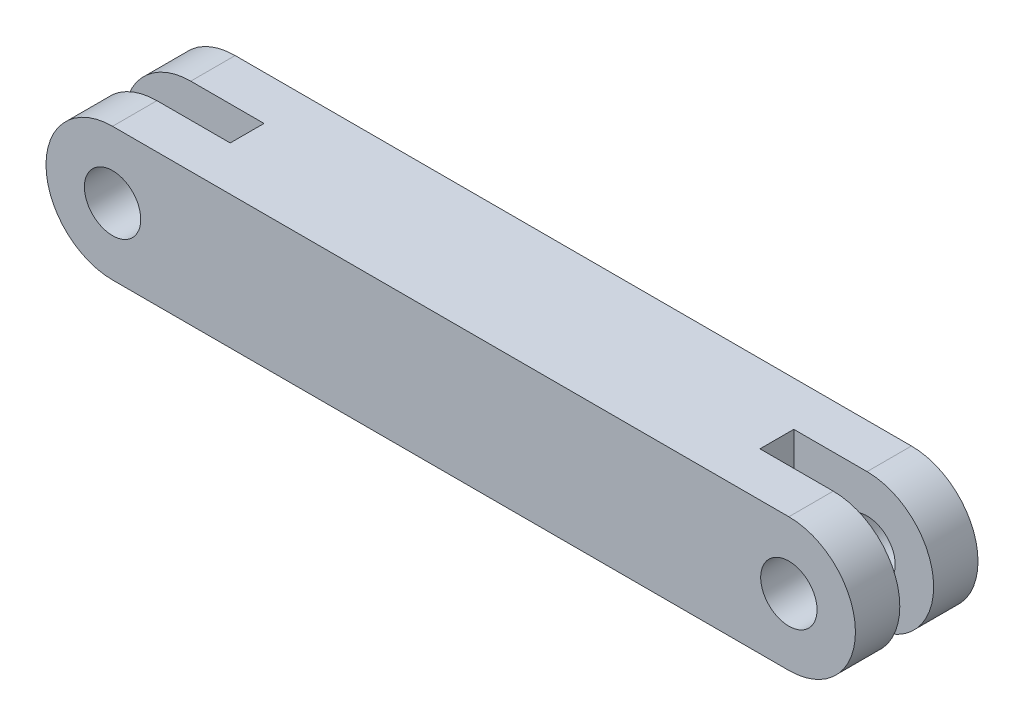
SolidWorks part; units mm, degrees
ref_plane "Front" through (0, 0, 0) normal (0, 0, 1) x (1, 0, 0)
ref_plane "Top" through (0, 0, 0) normal (0, 1, 0) x (1, 0, 0)
ref_plane "Right" through (0, 0, 0) normal (1, 0, 0) x (0, 0, -1)
sketch "Sketch1" plane through (0, 0, 0) normal (0, 0, 1) x (1, 0, 0)
  line L0 (-47.2174, 0.4239) -> (28.9826, 0.4239) construction
  line L1 (-47.2174, 7.9239) -> (28.9826, 7.9239)
  line L2 (-47.2174, -7.0761) -> (28.9826, -7.0761)
  arc A0 (-47.2174, 7.9239) -> (-47.2174, -7.0761) centre (-47.2174, 0.4239) ccw
  arc A1 (28.9826, -7.0761) -> (28.9826, 7.9239) centre (28.9826, 0.4239) ccw
  circle A2 centre (-47.2174, 0.4239) radius 3.175
  circle A3 centre (28.9826, 0.4239) radius 3.175
  point P2 (-9.1174, 0.4239)
  dimension "D1" = 7.5
  dimension "D3" = 6.35
  dimension "D4" = 6.35
  dimension "D2" = 76.2
extrude "Boss-Extrude1" add sketch "Sketch1" along normal blind 5
sketch "Sketch2" plane through (0, 0, 5) normal (0, 0, 1) x (1, 0, 0)
  line L2 (-38.9624, -7.0761) -> (-38.9624, 7.9239)
  line L4 (28.9826, 7.9239) -> (-47.2174, 7.9239) construction
  line L9 (20.7276, -7.0761) -> (20.7276, 7.9239)
  line L10 (-38.9624, 7.9239) -> (20.7276, 7.9239)
  line L11 (-38.9624, -7.0761) -> (20.7276, -7.0761)
  point P13 (-38.9624, 0.4239)
  point P16 (16.9972, 0.4239)
  point P24 (20.7276, 0.4239)
extrude "Boss-Extrude2" add sketch "Sketch2" along normal blind 3.81
sketch "Sketch5" plane through (0, 0, 8.81) normal (0, 0, 1) x (1, 0, 0)
  line L0 (-47.2174, 0.4239) -> (28.9826, 0.4239) construction
  line L1 (-47.2174, 7.9239) -> (28.9826, 7.9239)
  line L2 (-47.2174, -7.0761) -> (28.9826, -7.0761)
  arc A0 (-47.2174, 7.9239) -> (-47.2174, -7.0761) centre (-47.2174, 0.4239) ccw
  arc A1 (28.9826, -7.0761) -> (28.9826, 7.9239) centre (28.9826, 0.4239) ccw
  circle A2 centre (-47.2174, 0.4239) radius 3.175
  circle A3 centre (28.9826, 0.4239) radius 3.175
  point P4 (-9.1174, 0.4239)
  dimension "D1" = 7.5
  dimension "D2" = 6.35
  dimension "D3" = 6.35
extrude "Boss-Extrude3" add sketch "Sketch5" along normal blind 5
